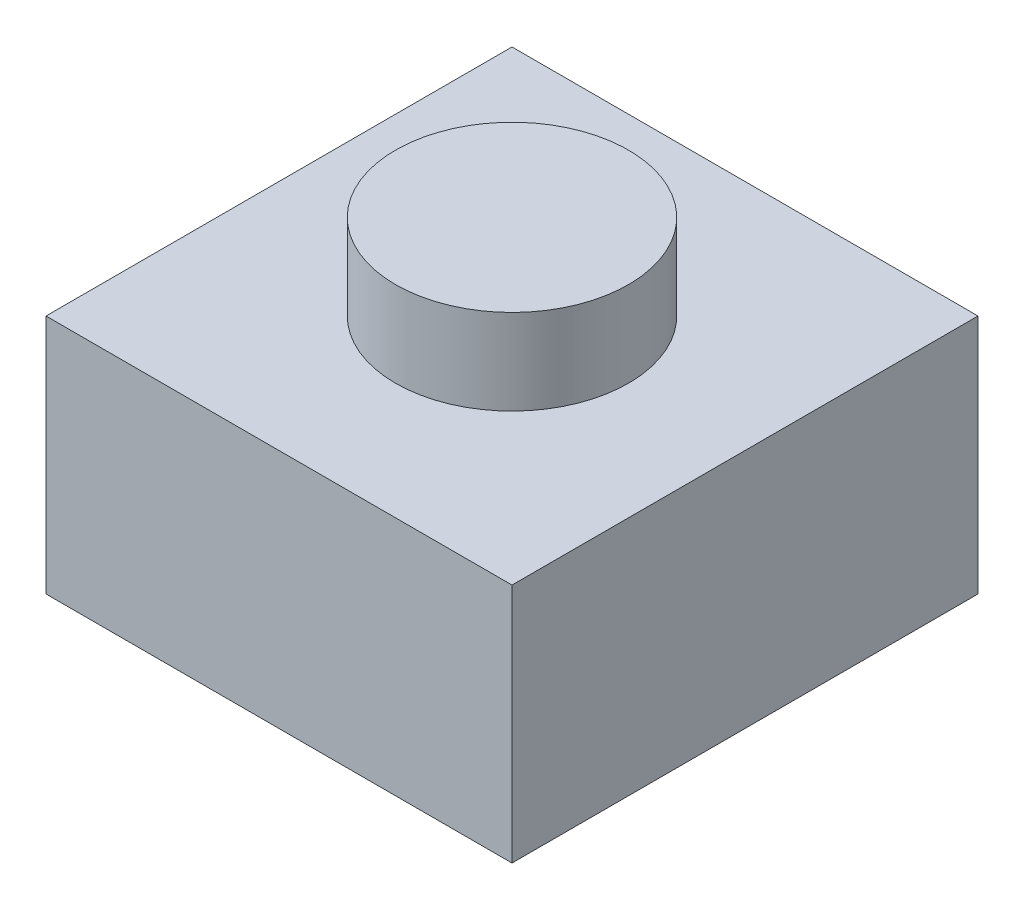
SolidWorks part; units mm, degrees
ref_plane "前视" through (0, 0, 0) normal (0, 0, 1) x (1, 0, 0)
ref_plane "上视" through (0, 0, 0) normal (0, 1, 0) x (1, 0, 0)
ref_plane "右视" through (0, 0, 0) normal (1, 0, 0) x (0, 0, -1)
sketch "草图1" plane through (0, 0, 0) normal (0, 1, 0) x (1, 0, 0)
  line L0 (0, 96.9306) -> (0, -101.3275) construction
  line L1 (-119.7143, 0) -> (134.9034, 0) construction
  line L3 (-3, 3) -> (3, 3)
  line L4 (-3, 3) -> (-3, -3)
  line L5 (-3, -3) -> (3, -3)
  line L6 (3, 3) -> (3, -3)
  dimension "D1" = 6
  dimension "D2" = 6
extrude "拉伸1" add sketch "草图1" along normal blind 3.1
sketch "草图2" plane through (0, 3.1, 0) normal (0, 1, 0) x (-1, 0, 0)
  line L0 (-3, 0) -> (8.7109, 0) construction
  line L1 (-3, 3) -> (-3, -3) construction
  line L2 (0, -7.8518) -> (0, 10.0992) construction
  circle A0 centre (0, 0) radius 1.5
  dimension "D1" = 3
extrude "拉伸2" add sketch "草图2" along normal offset from surface (1.1 mm away) 4.2 up to face at (0, 0, 0)
sketch "草图3" plane through (-3, 0, 0) normal (-1, 0, 0) x (0, 0, 1)
  line L0 (0, -6.9925) -> (0, 14.8526) construction
sketch "草图4" plane through (0, 4.2, 0) normal (0, 1, 0) x (-1, 0, 0)
  line L0 (0, -4.1469) -> (0, 4.9476) construction
  line L1 (-3.9082, 0) -> (5.1305, 0) construction
sketch "草图5" plane through (0, 0, 0) normal (0, -1, 0) x (1, 0, 0)
  line L0 (-4.4583, 0) -> (4.1341, 0) construction
  line L1 (0, 4.6756) -> (0, -4.3899) construction
